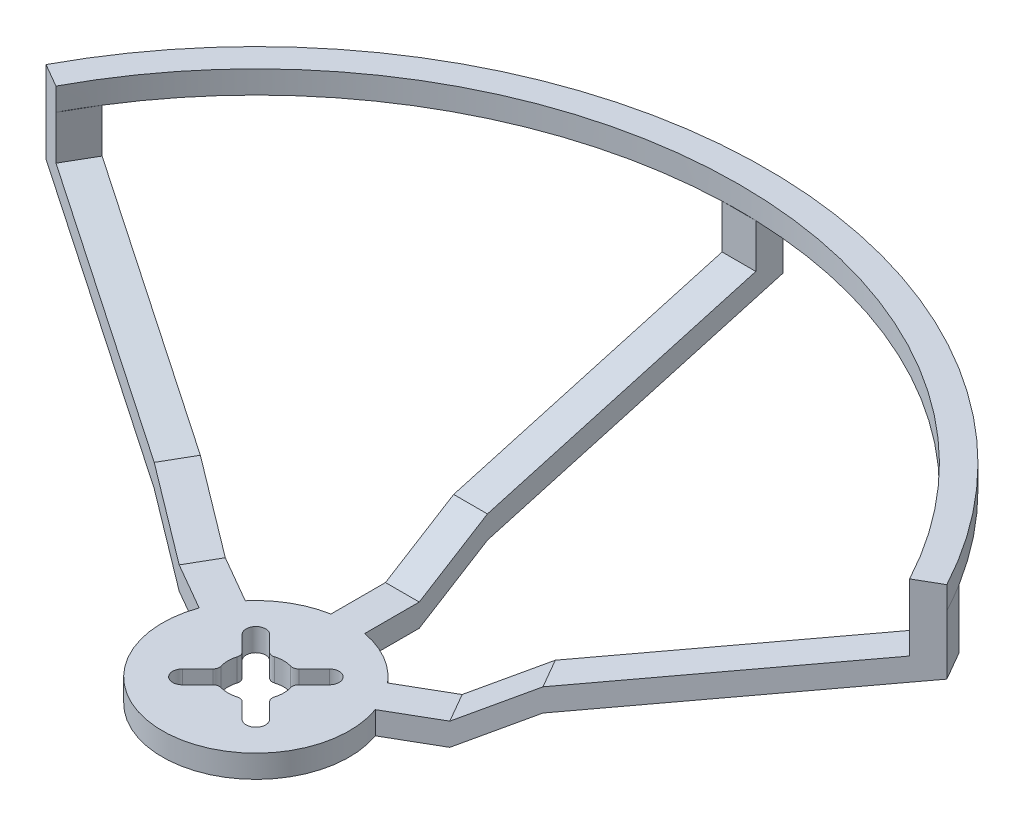
SolidWorks part; units mm, degrees
ref_plane "前视基准面" through (0, 0, 0) normal (0, 0, 1) x (1, 0, 0)
ref_plane "上视基准面" through (0, 0, 0) normal (0, 1, 0) x (1, 0, 0)
ref_plane "右视基准面" through (0, 0, 0) normal (1, 0, 0) x (0, 0, -1)
sketch "草图1" plane through (0, 0, 0) normal (0, 1, 0) x (1, 0, 0)
  line L0 (0, 0) -> (18.3003, 0) construction
  line L1 (0, 0) -> (0, 19.3424) construction
  line L2 (0, 0) -> (15.7713, 15.7713) construction
  line L3 (0, 0) -> (13.4075, -13.4075) construction
  line L4 (4.5962, 6.7175) -> (2.2439, 4.3652)
  line L5 (6.7175, 4.5962) -> (4.3652, 2.2439)
  line L6 (6.7175, -4.5962) -> (4.3652, -2.2439)
  line L7 (4.5962, -6.7175) -> (2.2439, -4.3652)
  line L8 (-4.5962, 6.7175) -> (-2.2439, 4.3652)
  line L9 (-6.7175, 4.5962) -> (-4.3652, 2.2439)
  line L10 (-4.5962, -6.7175) -> (-2.2439, -4.3652)
  line L11 (-6.7175, -4.5962) -> (-4.3652, -2.2439)
  line L12 (-2.6, 22.5633) -> (2.6, 22.5633)
  line L13 (2.6, 22.5633) -> (2.6, 14.1633)
  line L14 (-2.6, 22.5633) -> (-2.6, 14.1633)
  line L15 (18.2404, 13.5333) -> (20.8404, 9.03)
  line L16 (18.2404, 13.5333) -> (10.9658, 9.3333)
  line L17 (20.8404, 9.03) -> (13.5658, 4.83)
  line L18 (-20.8404, 9.03) -> (-18.2404, 13.5333)
  line L19 (-20.8404, 9.03) -> (-13.5658, 4.83)
  line L20 (-18.2404, 13.5333) -> (-10.9658, 9.3333)
  line L21 (0, 0) -> (-22.2979, 12.8737) construction
  line L22 (0, 0) -> (26.6894, 15.4092) construction
  arc A0 (-2.6, 14.1633) -> (-10.9658, 9.3333) centre (0, 0) ccw
  arc A1 (4.1153, -1.2468) -> (4.1153, 1.2468) centre (0, 0) ccw
  arc A2 (6.7175, 4.5962) -> (4.5962, 6.7175) centre (5.6569, 5.6569) ccw
  arc A3 (4.5962, -6.7175) -> (6.7175, -4.5962) centre (5.6569, -5.6569) ccw
  arc A4 (4.1153, -1.2468) -> (4.3652, -2.2439) centre (5.0723, -1.5368) ccw
  arc A5 (2.2439, -4.3652) -> (1.2468, -4.1153) centre (1.5368, -5.0723) ccw
  arc A6 (4.3652, 2.2439) -> (4.1153, 1.2468) centre (5.0723, 1.5368) ccw
  arc A7 (2.2439, 4.3652) -> (1.2468, 4.1153) centre (1.5368, 5.0723) cw
  arc A8 (1.2468, 4.1153) -> (-1.2468, 4.1153) centre (0, 0) ccw
  arc A9 (-4.5962, 6.7175) -> (-6.7175, 4.5962) centre (-5.6569, 5.6569) ccw
  arc A10 (-6.7175, -4.5962) -> (-4.5962, -6.7175) centre (-5.6569, -5.6569) ccw
  arc A11 (-2.2439, 4.3652) -> (-1.2468, 4.1153) centre (-1.5368, 5.0723) ccw
  arc A12 (-4.3652, 2.2439) -> (-4.1153, 1.2468) centre (-5.0723, 1.5368) cw
  arc A13 (-4.1153, 1.2468) -> (-4.1153, -1.2468) centre (0, 0) ccw
  arc A14 (-2.2439, -4.3652) -> (-1.2468, -4.1153) centre (-1.5368, -5.0723) cw
  arc A15 (-4.1153, -1.2468) -> (-4.3652, -2.2439) centre (-5.0723, -1.5368) cw
  arc A16 (-1.2468, -4.1153) -> (1.2468, -4.1153) centre (0, 0) ccw
  arc A17 (-13.5658, 4.83) -> (13.5658, 4.83) centre (0, 0) ccw
  arc A18 (10.9658, 9.3333) -> (2.6, 14.1633) centre (0, 0) ccw
  point P52 (0, 0)
  point P58 (0, 0)
  dimension "D1" = 28.8
  dimension "D2" = 8.6
  dimension "D5" = 3
  dimension "D8" = 1
  dimension "D9" = 1
  dimension "D10" = 1
  dimension "D11" = 1
  dimension "D14" = 1
  dimension "D15" = 1
  dimension "D16" = 1
  dimension "D17" = 1
  dimension "D3" = 45
  dimension "D4" = 45
  dimension "D6" = 8
  dimension "D7" = 8
  dimension "D12" = 8
  dimension "D13" = 8
  dimension "D18" = 5.2
  dimension "D19" = 2.6
  dimension "D20" = 8.4
  dimension "D23" = 60
  dimension "D24" = 60
  dimension "D25" = 60
  dimension "D21" = 2
  dimension "D22" = 2
extrude "凸台-拉伸1" add sketch "草图1" along normal blind 3.5
sketch "草图2" plane through (0, 0, 0) normal (1, 0, 0) x (0, 0, -1)
  line L0 (22.5633, 3.5) -> (33.0633, 10)
  line L1 (22.5633, 3.5) -> (14.1633, 3.5) construction
  line L2 (22.5633, 0) -> (33.0633, 6.5)
  line L3 (33.0633, 6.5) -> (78.6, 19.36)
  line L4 (33.0633, 10) -> (74.4, 21.6739)
  line L5 (78.6, 19.36) -> (78.6, 28.46)
  line L6 (74.4, 21.6739) -> (74.4, 28.46)
  line L7 (78.6, 28.46) -> (74.4, 28.46)
  line L8 (22.5633, 3.5) -> (22.5633, 0)
  point P7 (33.0633, 6.558)
  point P11 (0, 0)
  dimension "D1" = 4.2
  dimension "D3" = 28.46
  dimension "D4" = 93
  dimension "D5" = 10.5
  dimension "D6" = 9.1
  dimension "D7" = 10
extrude "凸台-拉伸2" add sketch "草图2" along normal mid plane 5.2
pattern_circular "阵列(圆周)1" count 2 every 60 about axis through (0, 3.5, 0) along (0, 1, 0) of "凸台-拉伸2"
pattern_circular "阵列(圆周)2" count 2 every 60 about axis through (0, 3.5, 0) along (0, 1, 0) of "凸台-拉伸2"
sketch "草图3" plane through (0, 28.46, 0) normal (0, 1, 0) x (1, 0, 0)
  line L2 (69.3696, 37.0483) -> (65.7323, 34.9483) construction
  line L4 (-69.3696, 37.0483) -> (-65.7323, 34.9483) construction
  line L5 (-69.3696, 37.0483) -> (-65.7323, 34.9483)
  line L6 (69.3696, 37.0483) -> (65.7323, 34.9483)
  arc A0 (-69.3696, 37.0483) -> (69.3696, 37.0483) centre (0, 0) cw
  arc A1 (-65.7323, 34.9483) -> (65.7323, 34.9483) centre (0, 0) cw
extrude "凸台-拉伸3" add sketch "草图3" along normal blind 3.5
